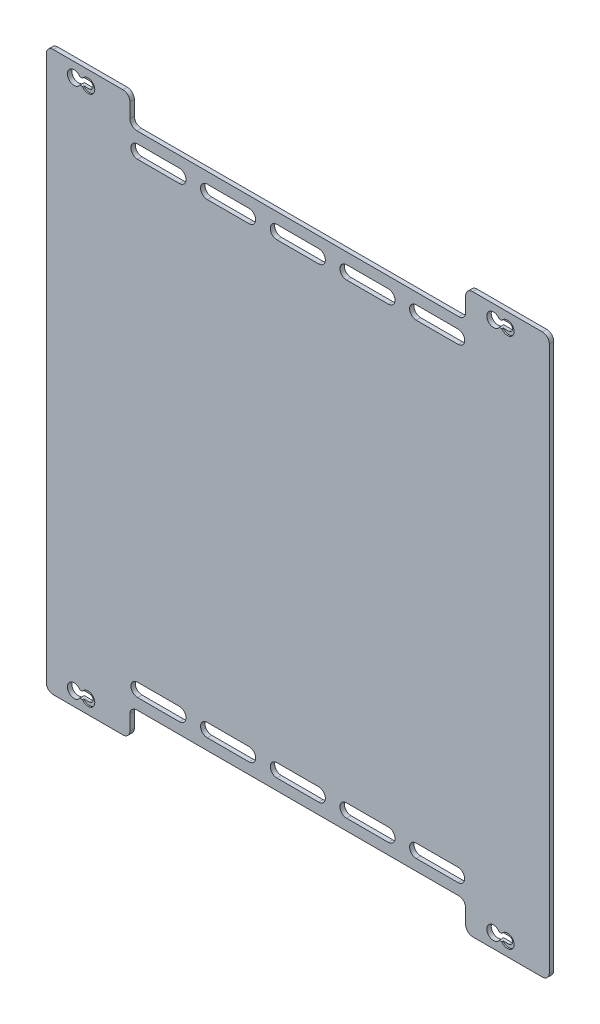
SolidWorks part; units mm, degrees
ref_plane "Front Plane" through (0, 0, 0) normal (0, 0, 1) x (1, 0, 0)
ref_plane "Top Plane" through (0, 0, 0) normal (0, 1, 0) x (1, 0, 0)
ref_plane "Right Plane" through (0, 0, 0) normal (1, 0, 0) x (0, 0, -1)
sketch "Model" plane through (0, 0, 0) normal (0, 0, 1) x (1, 0, 0)
  line L0 (175.5, 200.5049) -> (125.5, 200.5049)
  line L1 (144.6008, 187.9152) -> (150.5, 187.9152)
  line L2 (-175.5, 200.5049) -> (-125.5, 200.5049)
  line L3 (-115.5, 180) -> (115.5, 180)
  line L4 (-120.5, 185) -> (-120.5, 195.5049)
  line L5 (150.5, 193.0945) -> (144.6008, 193.0945)
  line L6 (150.5, -187.9055) -> (144.6008, -187.9055)
  line L7 (-180.5, -195.5049) -> (-180.5, 195.5049)
  line L8 (-120.5, -185) -> (-120.5, -195.5049)
  line L9 (-175.5, -200.5049) -> (-125.5, -200.5049)
  line L10 (-115.5, -180) -> (115.5, -180)
  line L11 (144.6008, -193.0848) -> (150.5, -193.0848)
  line L12 (-150.5, -187.9055) -> (-156.3992, -187.9055)
  line L13 (-156.3992, -193.0848) -> (-150.5, -193.0848)
  line L15 (120.5, 185) -> (120.5, 195.5049)
  line L16 (120.5, -185) -> (120.5, -195.5049)
  line L17 (175.5, -200.5049) -> (125.5, -200.5049)
  line L23 (180.5, 195.5049) -> (180.5, -195.5049)
  line L1211 (-150.5, 193.0945) -> (-156.3992, 193.0945)
  line L1300 (-156.3992, 187.9152) -> (-150.5, 187.9152)
  arc A0 (120.5, -195.5049) -> (125.5, -200.5049) centre (125.5, -195.5049) ccw
  arc A1 (175.5, -200.5049) -> (180.5, -195.5049) centre (175.5, -195.5049) ccw
  arc A2 (180.5, 195.5049) -> (175.5, 200.5049) centre (175.5, 195.5049) ccw
  arc A3 (120.5, 195.5049) -> (125.5, 200.5049) centre (125.5, 195.5049) cw
  arc A4 (120.5, 185) -> (115.5, 180) centre (115.5, 185) cw
  arc A5 (-120.5, 185) -> (-115.5, 180) centre (-115.5, 185) ccw
  arc A6 (-125.5, -200.5049) -> (-120.5, -195.5049) centre (-125.5, -195.5049) ccw
  arc A7 (-115.5, -180) -> (-120.5, -185) centre (-115.5, -185) ccw
  arc A8 (-180.5, -195.5049) -> (-175.5, -200.5049) centre (-175.5, -195.5049) ccw
  arc A9 (-120.5, 195.5049) -> (-125.5, 200.5049) centre (-125.5, 195.5049) ccw
  arc A10 (-175.5, 200.5049) -> (-180.5, 195.5049) centre (-175.5, 195.5049) ccw
  arc A11 (-150.5, 187.9152) -> (-150.5, 193.0945) centre (-150.5, 190.5049) ccw
  arc A12 (120.5, -185) -> (115.5, -180) centre (115.5, -185) ccw
  arc A13 (144.6008, 193.0945) -> (144.6008, 187.9152) centre (140.5, 190.5049) ccw
  arc A14 (150.5, 187.9152) -> (150.5, 193.0945) centre (150.5, 190.5049) ccw
  arc A15 (146.3992, 187.9152) -> (146.3992, 193.0945) centre (150.5, 190.5049) ccw construction
  arc A16 (144.6008, -187.9055) -> (144.6008, -193.0848) centre (140.5, -190.4951) ccw
  arc A17 (146.3992, -193.0848) -> (146.3992, -187.9055) centre (150.5, -190.4951) ccw construction
  arc A18 (150.5, -193.0848) -> (150.5, -187.9055) centre (150.5, -190.4951) ccw
  arc A19 (-154.6008, -193.0848) -> (-154.6008, -187.9055) centre (-150.5, -190.4951) ccw construction
  arc A20 (-150.5, -193.0848) -> (-150.5, -187.9055) centre (-150.5, -190.4951) ccw
  arc A21 (-156.3992, -187.9055) -> (-156.3992, -193.0848) centre (-160.5, -190.4951) ccw
  arc A31 (-154.6008, 187.9152) -> (-154.6008, 193.0945) centre (-150.5, 190.5049) ccw construction
  arc A32 (-156.3992, 193.0945) -> (-156.3992, 187.9152) centre (-160.5, 190.5049) ccw
  dimension "D1" = 360
  dimension "D11" = 5
  dimension "D12" = 4.85
  dimension "D13" = 4.85
  dimension "D17" = 5
  dimension "D18" = 5
  dimension "D19" = 5
  dimension "D20" = 5
  dimension "D21" = 5
  dimension "D22" = 5
  dimension "D23" = 5
  dimension "D24" = 5
  dimension "D25" = 5
  dimension "D26" = 5
  dimension "D27" = 5
  dimension "D29" = 10
  dimension "D31" = 20
  dimension "D2" = 180
  dimension "D3" = 361
  dimension "D4" = 180.5
  dimension "D5" = 60
  dimension "D6" = 60
  dimension "D7" = 20.5049
  dimension "D8" = 20.5049
  dimension "D9" = 20.5049
  dimension "D10" = 20.5049
  dimension "D14" = 10
  dimension "D15" = 60
  dimension "D16" = 60
  dimension "D28" = 10
  dimension "D30" = 5.1793
  dimension "D32" = 2
  dimension "D33" = 2
extrude "Boss-Extrude1" add sketch "Model" along normal blind 3.175
sketch "Sketch2" plane through (0, 0, 3.175) normal (0, 0, 1) x (1, 0, 0)
  circle A0 centre (-150.5, 190.5049) radius 4.8
  circle A1 centre (150.5, 190.5049) radius 4.8
  circle A2 centre (150.5, -190.4951) radius 4.8
  circle A3 centre (-150.5, -190.4951) radius 4.8
  dimension "D1" = 9.6
extrude "Cut-Extrude1" cut sketch "Sketch2" against normal blind 1
sketch "Sketch3" plane through (0, 0, 3.175) normal (0, 0, 1) x (1, 0, 0)
  line L0 (-15, 162.5) -> (15, 162.5)
  line L1 (-150, -150) -> (150, -150) construction
  line L2 (-150, -150) -> (-150, 150) construction
  line L3 (-150, 150) -> (150, 150) construction
  line L4 (150, -150) -> (150, 150) construction
  line L5 (-150, -150) -> (150, 150) construction
  line L6 (-150, 150) -> (150, -150) construction
  line L7 (-15, 172.025) -> (15, 172.025)
  line L8 (35, 172.025) -> (65, 172.025)
  line L9 (35, 162.5) -> (65, 162.5)
  line L10 (85, 172.025) -> (115, 172.025)
  line L11 (85, 162.5) -> (115, 162.5)
  line L14 (-65, 172.025) -> (-35, 172.025)
  line L15 (-65, 162.5) -> (-35, 162.5)
  line L16 (-115, 172.025) -> (-85, 172.025)
  line L17 (-115, 162.5) -> (-85, 162.5)
  line L20 (-180.5, 0) -> (180.5, 0) construction
  line L21 (-180.5, 195.5049) -> (-180.5, -195.5049) construction
  line L22 (180.5, -195.5049) -> (180.5, 195.5049) construction
  line L25 (-115, -162.5) -> (-85, -162.5)
  line L26 (-115, -172.025) -> (-85, -172.025)
  line L27 (-65, -162.5) -> (-35, -162.5)
  line L28 (-65, -172.025) -> (-35, -172.025)
  line L31 (85, -162.5) -> (115, -162.5)
  line L32 (85, -172.025) -> (115, -172.025)
  line L33 (35, -162.5) -> (65, -162.5)
  line L34 (35, -172.025) -> (65, -172.025)
  line L35 (-15, -172.025) -> (15, -172.025)
  line L36 (-15, -162.5) -> (15, -162.5)
  arc A0 (15, 172.025) -> (15, 162.5) centre (15, 167.2625) cw
  arc A1 (-15, 162.5) -> (-15, 172.025) centre (-15, 167.2625) cw
  arc A2 (35, 162.5) -> (35, 172.025) centre (35, 167.2625) cw
  arc A3 (65, 172.025) -> (65, 162.5) centre (65, 167.2625) cw
  arc A4 (85, 162.5) -> (85, 172.025) centre (85, 167.2625) cw
  arc A5 (115, 172.025) -> (115, 162.5) centre (115, 167.2625) cw
  arc A8 (-65, 162.5) -> (-65, 172.025) centre (-65, 167.2625) cw
  arc A9 (-35, 172.025) -> (-35, 162.5) centre (-35, 167.2625) cw
  arc A10 (-115, 162.5) -> (-115, 172.025) centre (-115, 167.2625) cw
  arc A11 (-85, 172.025) -> (-85, 162.5) centre (-85, 167.2625) cw
  arc A16 (-85, -172.025) -> (-85, -162.5) centre (-85, -167.2625) ccw
  arc A17 (-115, -162.5) -> (-115, -172.025) centre (-115, -167.2625) ccw
  arc A18 (-35, -172.025) -> (-35, -162.5) centre (-35, -167.2625) ccw
  arc A19 (-65, -162.5) -> (-65, -172.025) centre (-65, -167.2625) ccw
  arc A22 (115, -172.025) -> (115, -162.5) centre (115, -167.2625) ccw
  arc A23 (85, -162.5) -> (85, -172.025) centre (85, -167.2625) ccw
  arc A24 (65, -172.025) -> (65, -162.5) centre (65, -167.2625) ccw
  arc A25 (35, -162.5) -> (35, -172.025) centre (35, -167.2625) ccw
  arc A26 (-15, -162.5) -> (-15, -172.025) centre (-15, -167.2625) ccw
  arc A27 (15, -172.025) -> (15, -162.5) centre (15, -167.2625) ccw
  point P0 (0, 0)
  point P12 (0, 162.5)
  dimension "D3" = 4.7625
  dimension "D4" = 30
  dimension "D1" = 300
  dimension "D2" = 300
  dimension "D5" = 25
  dimension "D6" = 3
  dimension "D7" = 3
extrude "Cut-Extrude2" cut sketch "Sketch3" against normal up to surface (3.175 mm away) up to face at (-155.0399, 190.5049, 0)
